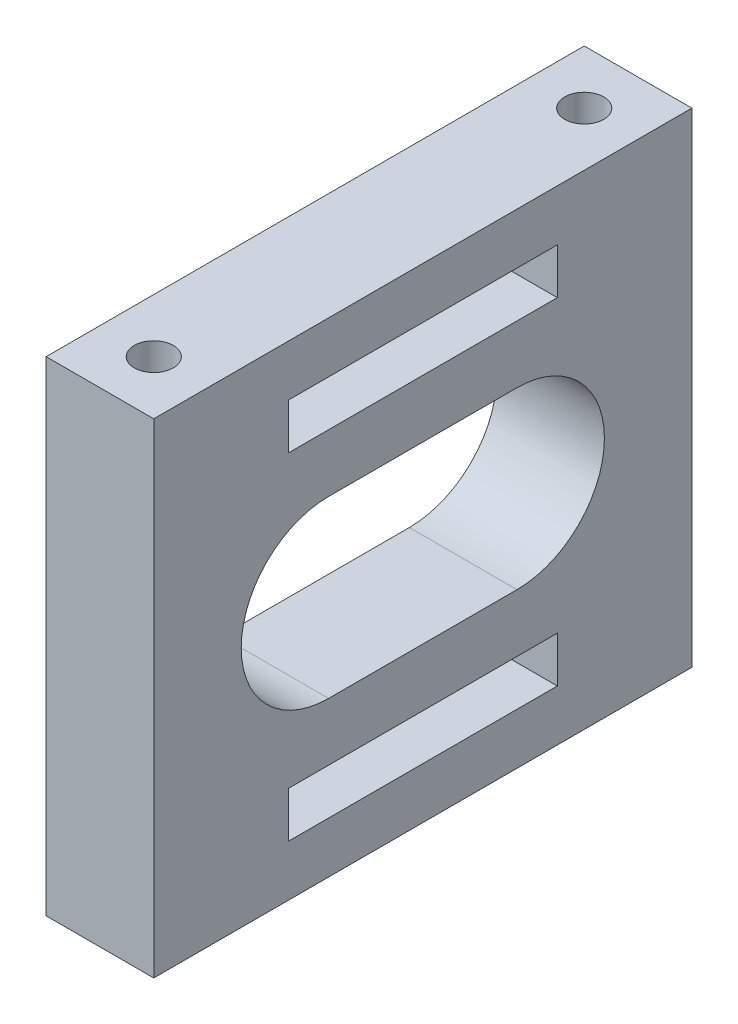
SolidWorks part; units mm, degrees
ref_plane "Front" through (0, 0, 0) normal (0, 0, 1) x (1, 0, 0)
ref_plane "Top" through (0, 0, 0) normal (0, 1, 0) x (1, 0, 0)
ref_plane "Right" through (0, 0, 0) normal (1, 0, 0) x (0, 0, -1)
sketch "Sketch1" plane through (0, 0, 0) normal (1, 0, 0) x (0, 0, -1)
  line L1 (0, 0) -> (40, 0)
  line L2 (0, 0) -> (0, -36)
  line L3 (0, -36) -> (40, -36)
  line L4 (40, 0) -> (40, -36)
  dimension "D1" = 40
  dimension "D2" = 36
extrude "Boss-Extrude1" add sketch "Sketch1" along normal blind 8
sketch "Sketch2" plane through (8, 0, 0) normal (1, 0, 0) x (0, 0, -1)
  line L0 (40, 0) -> (0, 0) construction
  line L1 (0, 0) -> (0, -36) construction
  circle A0 centre (20, -18) radius 6
  dimension "D1" = 12
  dimension "D2" = 18
  dimension "D3" = 20
extrude "Cut-Extrude1" cut sketch "Sketch2" against normal through all
sketch "Sketch3" plane through (8, 0, 0) normal (1, 0, 0) x (0, 0, -1)
  line L0 (40, -36) -> (40, 0) construction
  line L1 (10, -3.8) -> (30, -3.8)
  line L2 (10, -3.8) -> (10, -7.2)
  line L3 (10, -7.2) -> (30, -7.2)
  line L4 (30, -3.8) -> (30, -7.2)
  line L5 (40, 0) -> (0, 0) construction
  line L6 (10, -32.2) -> (30, -32.2)
  line L7 (10, -28.8) -> (30, -28.8)
  line L8 (30, -28.8) -> (30, -32.2)
  line L9 (10, -28.8) -> (10, -32.2)
  dimension "D1" = 3.4
  dimension "D2" = 20
  dimension "D3" = 10
  dimension "D4" = 3.8
  dimension "D5" = 2
extrude "Cut-Extrude2" cut sketch "Sketch3" against normal through all
sketch "Sketch6" plane through (0, 0, 0) normal (0, 1, 0) x (1, 0, 0)
  line L0 (8, 40) -> (8, 0) construction
  line L1 (8, 0) -> (0, 0) construction
  circle A0 centre (4, 4) radius 1.45
  circle A1 centre (4, 36) radius 1.45
  dimension "D1" = 2.9
  dimension "D2" = 4
  dimension "D3" = 4
  dimension "D4" = 2
extrude "Cut-Extrude3" cut sketch "Sketch6" against normal through all
sketch "Sketch7" plane through (8, 0, 0) normal (1, 0, 0) x (0, 0, -1)
  line L0 (0, -36) -> (40, -36) construction
  line L1 (13, -24.5) -> (27, -24.5)
  line L2 (0, 0) -> (0, -36) construction
  line L3 (40, -36) -> (40, 0) construction
  line L4 (13, -11.5) -> (27, -11.5)
  line L5 (27, -24.5) -> (27, -11.5)
  line L6 (13, -24.5) -> (13, -11.5)
  circle A0 centre (27, -18) radius 6.5
  circle A1 centre (13, -18) radius 6.5
  dimension "D5" = 13
  dimension "D6" = 13
  dimension "D1" = 18
  dimension "D2" = 18
  dimension "D3" = 13
  dimension "D4" = 13
extrude "Cut-Extrude4" cut sketch "Sketch7" against normal through all contours A1 | L1 L5 L4 L6 | A0
equation "\"offset\"= 0.4"
equation "\"D1@Sketch3\"=\"offset\"+3"
equation "\"滑动-垂直孔\" = 0.6"
equation "\"滑动-水平孔\"= 0.3"
equation "\"松动-垂直孔\" = 0.3"
equation "\"松动-水平孔\"= 0.1"
equation "\"正常-垂直孔\" = 0.15"
equation "\"正常-水平孔\"= 0"
equation "\"紧缩-垂直孔\"= 0"
equation "\"紧缩-水平孔\"= - 0.1"
equation "\"D1@Sketch6\"=\"紧缩-水平孔\"+3"
